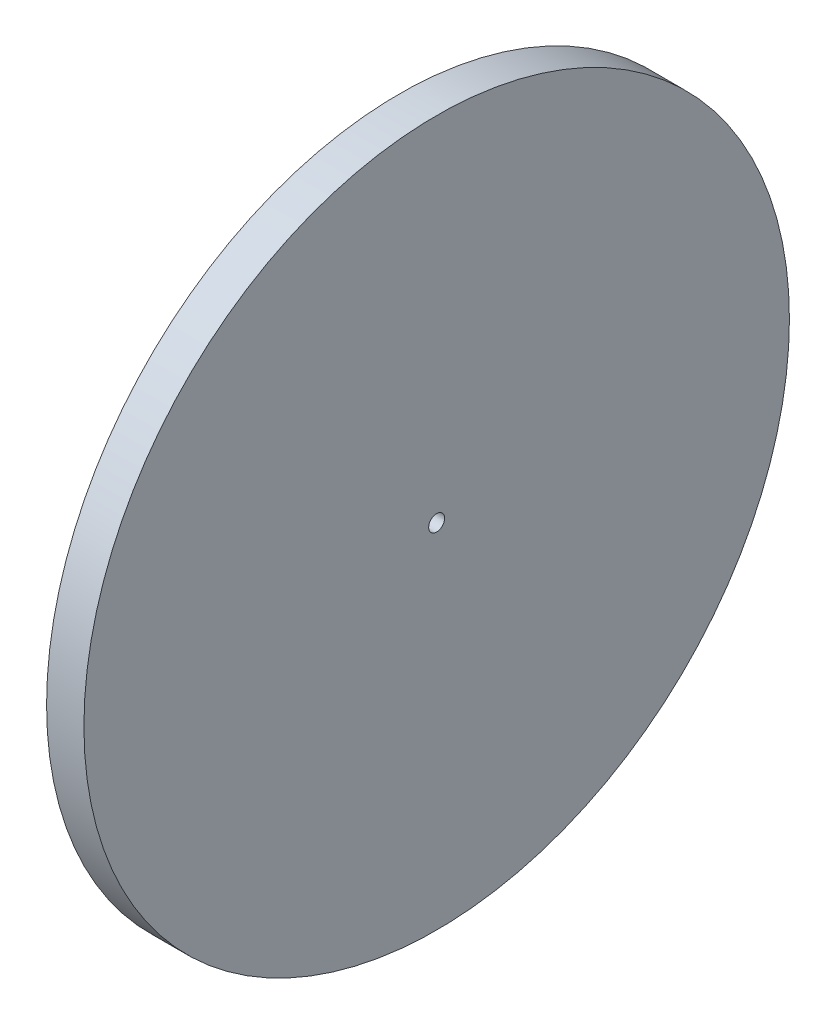
SolidWorks part; units mm, degrees
ref_plane "Front Plane" through (0, 0, 0) normal (0, 0, 1) x (1, 0, 0)
ref_plane "Top Plane" through (0, 0, 0) normal (0, 1, 0) x (1, 0, 0)
ref_plane "Right Plane" through (0, 0, 0) normal (1, 0, 0) x (0, 0, -1)
sketch "Sketch1" plane through (0, 0, 0) normal (1, 0, 0) x (0, 0, -1)
  circle A0 centre (-1.7759, 2.6639) radius 30
  circle A1 centre (-1.7759, 2.6639) radius 0.678
extrude "Extrude1" add sketch "Sketch1" along normal blind 3.175
